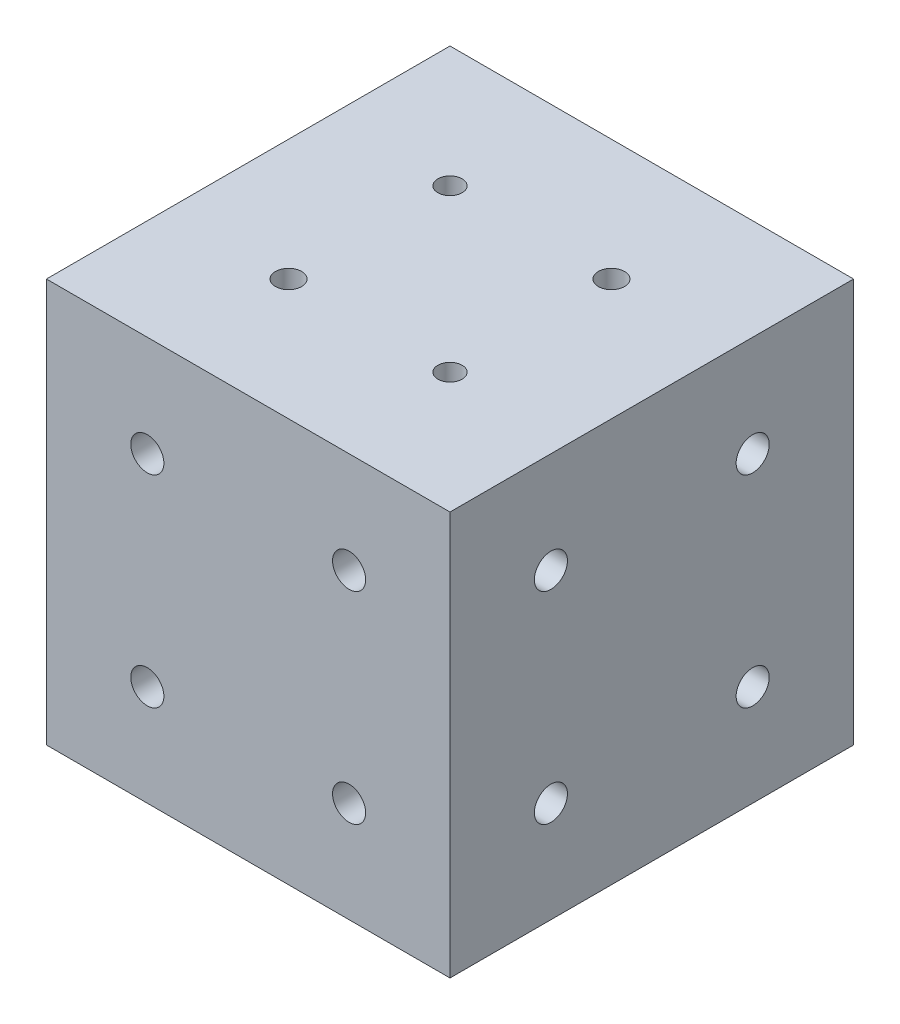
SolidWorks part; units mm, degrees
material "6061 Alloy"
ref_plane "Front Plane" through (0, 0, 0) normal (0, 0, 1) x (1, 0, 0)
ref_plane "Top Plane" through (0, 0, 0) normal (0, 1, 0) x (1, 0, 0)
ref_plane "Right Plane" through (0, 0, 0) normal (1, 0, 0) x (0, 0, -1)
sketch "Sketch1" plane through (0, 0, 0) normal (0, 0, 1) x (1, 0, 0)
  line L1 (-50, -50) -> (50, -50)
  line L2 (-50, -50) -> (-50, 50)
  line L3 (-50, 50) -> (50, 50)
  line L4 (50, -50) -> (50, 50)
  line L5 (-50, -50) -> (50, 50) construction
  line L6 (-50, 50) -> (50, -50) construction
  point P0 (0, 0)
  point P14 (0, 0)
  point P15 (0, 0)
  point P16 (0, 0)
  point P17 (0, 0)
  dimension "D1" = 100
extrude "Boss-Extrude1" add sketch "Sketch1" along normal mid plane 100
sketch "Sketch2" plane through (0, 0, 50) normal (0, 0, 1) x (1, 0, 0)
  line L1 (-25, -25) -> (25, -25) construction
  line L2 (-25, -25) -> (-25, 25) construction
  line L3 (-25, 25) -> (25, 25) construction
  line L4 (25, -25) -> (25, 25) construction
  line L5 (-25, -25) -> (25, 25) construction
  line L6 (-25, 25) -> (25, -25) construction
  circle A0 centre (-25, 25) radius 4.1
  circle A1 centre (25, 25) radius 4.1
  circle A2 centre (25, -25) radius 4.1
  circle A3 centre (-25, -25) radius 4.1
  point P0 (0, 0)
  dimension "D2" = 8.2
  dimension "D1" = 50
extrude "Cut-Extrude1" cut sketch "Sketch2" against normal through all
sketch "Sketch3" plane through (50, 0, 0) normal (1, 0, 0) x (0, 0, -1)
  line L1 (-25, -25) -> (25, -25) construction
  line L2 (-25, -25) -> (-25, 25) construction
  line L3 (-25, 25) -> (25, 25) construction
  line L4 (25, -25) -> (25, 25) construction
  line L5 (-25, -25) -> (25, 25) construction
  line L6 (-25, 25) -> (25, -25) construction
  circle A0 centre (-25, 25) radius 4.1
  circle A1 centre (25, 25) radius 4.1
  circle A2 centre (25, -25) radius 4.1
  circle A3 centre (-25, -25) radius 4.1
  point P0 (0, 0)
  point P10 (0, 0)
  dimension "D2" = 8.2
  dimension "D1" = 50
extrude "Cut-Extrude2" cut sketch "Sketch3" against normal through all
sketch "Sketch4" plane through (0, 50, 0) normal (0, 1, 0) x (1, 0, 0)
  line L1 (-20, -20) -> (20, -20) construction
  line L2 (-20, -20) -> (-20, 20) construction
  line L3 (-20, 20) -> (20, 20) construction
  line L4 (20, -20) -> (20, 20) construction
  line L5 (-20, -20) -> (20, 20) construction
  line L6 (-20, 20) -> (20, -20) construction
  circle A0 centre (-20, 20) radius 3
  circle A1 centre (20, -20) radius 3
  circle A2 centre (20, 20) radius 3.25
  circle A3 centre (-20, -20) radius 3.25
  point P0 (0, 0)
  dimension "D2" = 6
  dimension "D3" = 6.5
  dimension "D1" = 40
extrude "Cut-Extrude3" cut sketch "Sketch4" against normal through all
sketch "Sketch8" plane through (0, 0, 0) normal (0, 1, 0) x (1, 0, 0)
  line L1 (-42.5, -42.5) -> (42.5, -42.5)
  line L2 (-42.5, -42.5) -> (-42.5, 42.5)
  line L3 (-42.5, 42.5) -> (42.5, 42.5)
  line L4 (42.5, -42.5) -> (42.5, 42.5)
  line L5 (-42.5, -42.5) -> (42.5, 42.5) construction
  line L6 (-42.5, 42.5) -> (42.5, -42.5) construction
  point P0 (0, 0)
  dimension "D1" = 85
extrude "Cut-Extrude4" cut sketch "Sketch8" against normal mid plane 80
